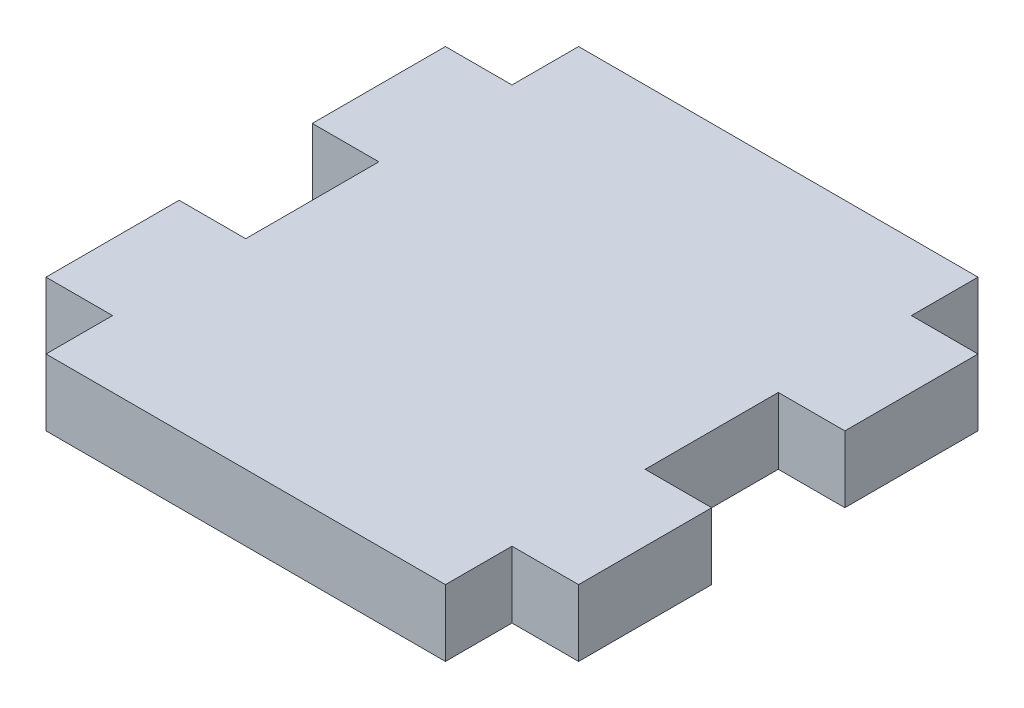
SolidWorks part; units mm, degrees
ref_plane "前视基准面" through (0, 0, 0) normal (0, 0, 1) x (1, 0, 0)
ref_plane "上视基准面" through (0, 0, 0) normal (0, 1, 0) x (1, 0, 0)
ref_plane "右视基准面" through (0, 0, 0) normal (1, 0, 0) x (0, 0, -1)
sketch "草图1" plane through (0, 0, 0) normal (0, 1, 0) x (1, 0, 0)
  line L0 (-5, 34.7751) -> (-5, -4.7751) construction
  line L1 (0, 0) -> (30, 0)
  line L2 (0, 0) -> (0, 5)
  line L3 (0, 40) -> (30, 40)
  line L4 (30, 0) -> (30, 5)
  line L5 (35, 44.7202) -> (35, -3.5987) construction
  line L6 (0, 35) -> (0, 40)
  line L7 (-5, 35) -> (0, 35)
  line L8 (-5, 35) -> (-5, 25)
  line L9 (-5, 25) -> (0, 25)
  line L10 (30, 35) -> (30, 40)
  line L11 (-5, 15) -> (0, 15)
  line L12 (-5, 15) -> (-5, 5)
  line L13 (-5, 5) -> (0, 5)
  line L15 (30, 35) -> (35, 35)
  line L16 (0, 15) -> (0, 25)
  line L17 (30, 25) -> (35, 25)
  line L18 (35, 35) -> (35, 25)
  line L19 (30, 15) -> (35, 15)
  line L21 (30, 5) -> (35, 5)
  line L22 (35, 15) -> (35, 5)
  line L23 (30, 15) -> (30, 25)
  dimension "D1" = 30
  dimension "D2" = 40
  dimension "D3" = 5
  dimension "D4" = 5
  dimension "D5" = 5
  dimension "D6" = 5
  dimension "D7" = 10
  dimension "D8" = 10
  dimension "D9" = 10
  dimension "D10" = 10
  dimension "D11" = 5
  dimension "D12" = 5
extrude "凸台-拉伸1" add sketch "草图1" along normal blind 5
